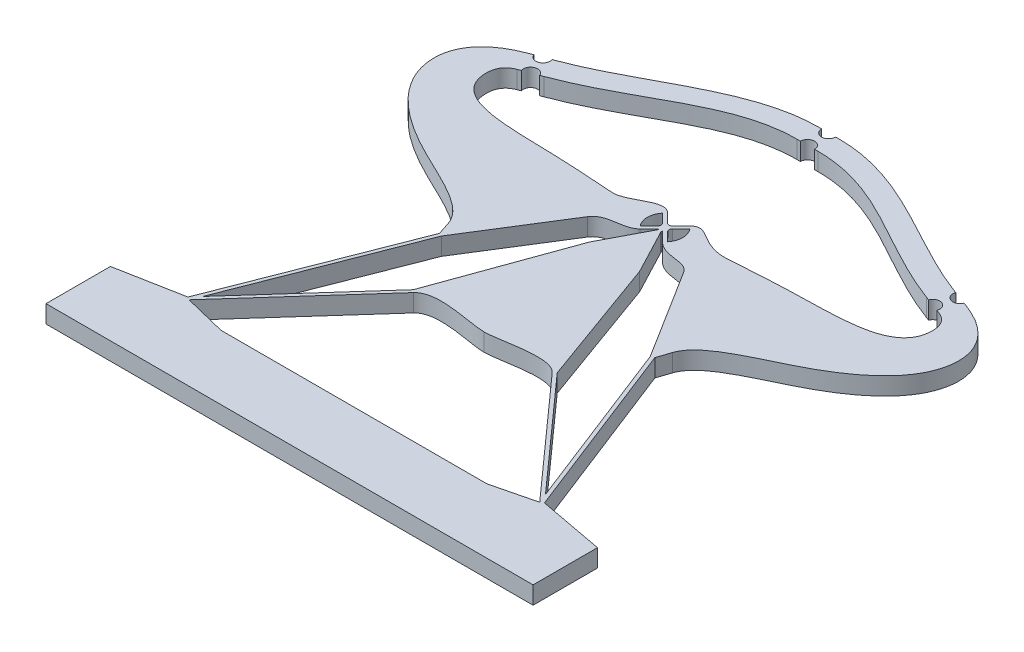
SolidWorks part; units mm, degrees
ref_plane "Front Plane" through (0, 0, 0) normal (0, 0, 1) x (1, 0, 0)
ref_plane "Top Plane" through (0, 0, 0) normal (0, 1, 0) x (1, 0, 0)
ref_plane "Right Plane" through (0, 0, 0) normal (1, 0, 0) x (0, 0, -1)
sketch "Basic" plane through (0, 0, 0) normal (0, 1, 0) x (1, 0, 0)
  line L0 (-100, 0) -> (-40, 67.082) construction
  line L1 (-40, 67.082) -> (0, 169.5515) construction
  line L2 (0, 169.5515) -> (-60, 102.4695) construction
  line L3 (-60, 102.4695) -> (-100, 0) construction
  line L4 (-40, 67.082) -> (40, 67.082) construction
  line L5 (-60, 102.4695) -> (-115.9233, 212.8627) construction
  line L6 (-115.9233, 212.8627) -> (0, 169.5515) construction
  line L7 (-115.9233, 212.8627) -> (0, 256.1738) construction
  line L8 (0, 256.1738) -> (0, 169.5515) construction
  line L9 (115.9233, 212.8627) -> (0, 256.1738) construction
  line L10 (115.9233, 212.8627) -> (0, 169.5515) construction
  line L11 (60, 102.4695) -> (115.9233, 212.8627) construction
  line L12 (60, 102.4695) -> (100, 0) construction
  line L13 (0, 169.5515) -> (60, 102.4695) construction
  line L14 (40, 67.082) -> (0, 169.5515) construction
  line L15 (100, 0) -> (40, 67.082) construction
  point P0 (-100, 0)
  point P1 (-40, 67.082)
  point P2 (0, 169.5515)
  point P14 (0, 67.082)
  point P15 (0, 0)
  dimension "l1/2" = 100
  dimension "l2" = 90
  dimension "l3/2" = 40
  dimension "couplerLength" = 110
  dimension "couplerAngle" = 68.676
  dimension "couplerAngle2" = 68.676
  dimension "D1" = 68.676
  dimension "OAngle" = 69.513
  dimension "D3" = 69.513
sketch "Sketch4" plane through (0, 0, 0) normal (0, 1, 0) x (1, 0, 0)
  line L0 (-100, 0) -> (-40, 67.082) construction
  line L1 (0, 256.1738) -> (0, 169.5515) construction
  line L2 (-60, 102.4695) -> (-100, 0) construction
  line L3 (-60.9315, 102.8331) -> (-100.9315, 0.3636)
  line L4 (-59.0685, 102.1059) -> (-97.0562, 4.7913)
  line L5 (-99.2546, -0.6667) -> (-39.2546, 66.4154)
  line L6 (-97.0562, 4.7913) -> (-40.7454, 67.7487)
  line L7 (-27.2733, 152.8134) -> (-59.0685, 102.1059)
  line L8 (-8.808, 205.2724) -> (8.808, 133.8307) construction
  line L9 (-100.9315, 0.3636) -> (-137.8734, -6.5819)
  line L10 (-8.989, 165.1701) -> (-28.2658, 154.55)
  line L11 (-99.2546, -0.6667) -> (-75.2651, -6.5819)
  line L12 (-6.4533, 162.591) -> (-40.7454, 67.7487)
  line L13 (-100.7454, 0.6667) -> (-40.7454, 67.7487) construction
  line L14 (-7.9358, 163.4669) -> (-27.2733, 152.8134)
  line L15 (0, 169.5515) -> (-60, 102.4695) construction
  line L16 (-115.9233, 212.8627) -> (0, 169.5515) construction
  line L17 (0, 169.5515) -> (42.4895, 180.0285) construction
  line L19 (-115.9233, 212.8627) -> (0, 256.1738) construction
  line L20 (-59.0685, 102.1059) -> (-99.0685, -0.3636) construction
  line L21 (-60.9315, 102.8331) -> (-63.4074, 110.2406)
  line L26 (-121.6167, 228.1012) -> (-109.5404, 195.7788) construction
  line L27 (-121.7702, 217.0832) -> (-123.6438, 216.3832)
  line L28 (-110.0763, 208.6421) -> (-108.2028, 209.3421)
  line L29 (-103.9501, 217.3361) -> (-126.2848, 208.9914) construction
  line L30 (-117.5704, 205.8422) -> (-119.4439, 205.1422)
  line L31 (-114.2762, 219.8831) -> (-112.4027, 220.5831)
  line L33 (-27.2733, 152.8134) -> (-7.9358, 163.4669)
  line L36 (-31.9283, 171.6919) -> (-9.8548, 171.2494)
  line L37 (-9.8548, 171.2494) -> (-31.9283, 171.6919)
  line L38 (12.8937, 256.1738) -> (-10.9489, 256.1738) construction
  line L39 (0, 265.543) -> (0, 231.0383) construction
  line L40 (4, 250.1738) -> (6, 250.1738) construction
  line L41 (4, 262.1738) -> (6, 262.1738) construction
  line L42 (-4, 250.1738) -> (-6, 250.1738)
  line L43 (-4, 262.1738) -> (-6, 262.1738)
  line L44 (-9.9955, 169.2518) -> (-31.9997, 169.693)
  line L54 (0, 185.8984) -> (-14.1025, 185.8984) construction
  line L55 (0, -6.5819) -> (-75.2651, -6.5819)
  line L56 (-137.8734, -6.5819) -> (-137.8734, -43.045)
  line L57 (-40, 67.082) -> (40, 67.082) construction
  line L58 (-137.8734, -43.045) -> (0, -43.045)
  line L60 (0, -6.5819) -> (0, -43.045)
  line L61 (0, 185.8984) -> (0, 67.082)
  line L62 (0, 258.1738) -> (0, 254.1738)
  arc A2 (-6.4533, 162.591) -> (-7.9358, 163.4669) centre (-7.4533, 162.591) ccw
  arc A5 (-31.9997, 169.693) -> (-28.2658, 154.55) centre (0, 169.5515) ccw
  arc A8 (-121.7702, 217.0832) -> (-114.2762, 219.8831) centre (-118.0232, 218.4832) ccw
  arc A9 (-117.5704, 205.8422) -> (-110.0763, 208.6421) centre (-113.8234, 207.2421) cw
  arc A12 (-4, 250.1738) -> (0, 254.1738) centre (0, 250.1738) cw
  arc A13 (-4, 262.1738) -> (0, 258.1738) centre (0, 262.1738) ccw
  arc A16 (-8.989, 165.1701) -> (-9.9955, 169.2518) centre (0, 169.5515) cw
  arc A17 (-8.9494, 172.7141) -> (-9.8548, 171.2494) centre (-9.8348, 172.2492) cw
  spline S0 degree 3 poles (-108.2028, 209.3421) (-69.2396, 223.8995) (-42.6858, 250.1738) (-6, 250.1738) knots 0 0 0 0 1 1 1 1
  spline S1 degree 3 poles (-112.4027, 220.5831) (-76.7304, 233.911) (-44.0894, 262.1738) (-6, 262.1738) knots 0 0 0 0 1 1 1 1
  spline S3 degree 3 poles (-119.4439, 205.1422) (-125.6717, 202.8154) (-131.1957, 172.2284) (-78.3016, 175.6405) (-35.272, 171.759) (-31.9283, 171.6919) knots 0 0 0 0 0.124419 0.71001 1 1 1 1
  spline S4 degree 3 poles (-123.6438, 216.3832) (-146.4506, 207.8622) (-156.0924, 174.1496) (-112.6778, 138.1204) (-67.7469, 123.2236) (-63.4074, 110.2406) knots 0 0 0 0 0.283699 0.638824 1 1 1 1
  spline S10 degree 3 poles (-39.2546, 66.4154) (-32.2633, 74.2319) (-8.577, 67.082) (0, 67.082) knots 0 0 0 0 1 1 1 1
  spline S11 degree 3 poles (-8.9494, 172.7141) (-10.9706, 176.5634) (-7.6165, 181.239) (-4.8136, 185.8984) (0, 185.8984) knots 0 0 0 0 0.470593 1 1 1 1
  dimension "D6" = 10
  dimension "D11" = 10.198
  dimension "D21" = 4
  dimension "D31" = 4
  dimension "D7" = 32
  dimension "D10" = 1
  dimension "D13" = 1
  dimension "D8" = 1
  dimension "D4" = 1
  dimension "D5" = 1
  dimension "D9" = 2
  dimension "D12" = 15
  dimension "D22" = 6
  dimension "D23" = 8
  dimension "D24" = 2
  dimension "D25" = 2
  dimension "D32" = 6
  dimension "D33" = 8
  dimension "D34" = 2
  dimension "D35" = 2
sketch "Sketch5" plane through (0, 0, 0) normal (0, 1, 0) x (1, 0, 0)
  line L0 (-14.0529, 35.7209) -> (3.5631, -35.7209) construction
  line L1 (-14.234, -4.3814) -> (-33.5107, -15.0015)
  line L2 (-13.1807, -6.0846) -> (-32.5182, -16.7382)
  line L3 (-5.2449, 0) -> (37.2446, 10.477) construction
  line L4 (-32.5182, -16.7382) -> (-13.1807, -6.0846)
  line L5 (-32.8384, 16.2049) -> (-13.6886, 5.3576)
  line L6 (-33.7969, 14.4493) -> (-14.5868, 3.5678)
  line L7 (-37.1732, 2.1404) -> (-15.0997, 1.6979)
  line L8 (-15.0997, 1.6979) -> (-37.1732, 2.1404)
  line L9 (-15.2404, -0.2997) -> (-37.2446, 0.1414)
  line L10 (-23.8067, -26.0665) -> (-11.8573, -7.5017)
  line L11 (-22.1418, -27.1752) -> (-10.23, -8.6688)
  arc A0 (-11.8573, -7.5017) -> (-13.1807, -6.0846) centre (-12.6982, -6.9605) ccw
  arc A1 (-14.234, -4.3814) -> (-13.1807, -6.0846) centre (-5.2449, 0) ccw
  arc A2 (-11.8573, -7.5017) -> (-10.23, -8.6688) centre (-5.2449, 0) ccw
  arc A3 (-33.5107, -15.0015) -> (-32.5182, -16.7382) centre (-5.2449, 0) ccw
  arc A4 (-23.8067, -26.0665) -> (-22.1418, -27.1752) centre (-5.2449, 0) ccw
  arc A5 (-33.7969, 14.4493) -> (-32.8384, 16.2049) centre (-5.2449, 0) cw
  arc A6 (-37.2446, 0.1414) -> (-37.1732, 2.1404) centre (-5.2449, 0) cw
  arc A7 (-14.5868, 3.5678) -> (-13.6886, 5.3576) centre (-5.2449, 0) cw
  arc A8 (-14.234, -4.3814) -> (-15.2404, -0.2997) centre (-5.2449, 0) cw
  arc A9 (-14.5868, 3.5678) -> (-15.0997, 1.6979) centre (-15.0797, 2.6977) cw
  point P8 (-16.1859, -17.922)
  dimension "D1" = 64
  dimension "D4" = 1
  dimension "D7" = 10
  dimension "D2" = 2
  dimension "D3" = 2
  dimension "D5" = 10.198
  dimension "D6" = 15
extrude "Boss-Extrude1" add sketch "Sketch4" along normal blind 10
mirror "Mirror1" about plane through (0, 10, 0) normal (1, 0, 0) of bodies 101
sketch "Sketch6" plane through (0, 10, 0) normal (0, 1, 0) x (1, 0, 0)
  circle A0 centre (0, 169.5515) radius 32
extrude "Cut-Extrude1" cut sketch "Sketch6" against normal blind 10 contours A0
sketch "Sketch7" plane through (0, 10, 0) normal (0, 1, 0) x (1, 0, 0)
  line L0 (-7.0711, 176.6226) -> (7.0711, 162.4805) construction
  line L1 (-27.2733, 152.8134) -> (-59.0685, 102.1059) construction
  line L2 (7.0711, 176.6226) -> (-7.0711, 162.4805) construction
  line L4 (1, 166.2325) -> (14.2892, 140.9191)
  line L5 (6.364, 177.3297) -> (1.4142, 172.38)
  line L6 (-7.7782, 175.9155) -> (-2.8284, 170.9658)
  line L7 (7.7782, 175.9155) -> (2.8284, 170.9658)
  line L8 (-6.364, 177.3297) -> (-1.4142, 172.38)
  line L9 (1.4142, 166.7231) -> (6.364, 161.7734)
  line L10 (-2.8284, 168.1373) -> (-7.7782, 163.1876)
  line L11 (-7.7782, 175.9155) -> (6.364, 161.7734) construction
  line L12 (2.8284, 168.1373) -> (7.7782, 163.1876)
  line L13 (6.364, 177.3297) -> (-7.7782, 163.1876) construction
  line L14 (-1.4142, 166.7231) -> (-6.364, 161.7734)
  line L15 (-6.364, 177.3297) -> (7.7782, 163.1876) construction
  line L16 (27.2733, 152.8134) -> (59.0685, 102.1059) construction
  line L17 (7.7782, 175.9155) -> (-6.364, 161.7734) construction
  line L18 (-1, 166.2325) -> (-14.2892, 140.9191)
  line L20 (-1, 166.2325) -> (-1, 167.041)
  line L22 (1, 166.2325) -> (1, 167.041)
  line L23 (-1, 163.0509) -> (1, 167.5669) construction
  line L24 (-1, 167.5669) -> (1, 163.0509) construction
  arc A0 (-31.9283, 171.6919) -> (-27.2733, 152.8134) centre (0, 169.5515) ccw construction
  arc A1 (27.2733, 152.8134) -> (31.9283, 171.6919) centre (0, 169.5515) ccw construction
  arc A2 (7.7427, 163.223) -> (7.7427, 175.8801) centre (0, 169.5515) ccw
  arc A3 (-7.7427, 175.8801) -> (-7.7427, 163.223) centre (0, 169.5515) ccw
  arc A4 (27.2733, 152.8134) -> (31.9283, 171.6919) centre (0, 169.5515) ccw
  arc A5 (-31.9283, 171.6919) -> (-27.2733, 152.8134) centre (0, 169.5515) ccw
  arc A6 (-14.2892, 140.9191) -> (14.2892, 140.9191) centre (0, 169.5515) ccw construction
  arc A7 (-14.2892, 140.9191) -> (14.2892, 140.9191) centre (0, 169.5515) ccw
  arc A8 (-2.8284, 168.1373) -> (-2.8284, 170.9658) centre (-4.2426, 169.5515) ccw
  arc A9 (-1.4142, 172.38) -> (1.4142, 172.38) centre (0, 173.7942) ccw
  arc A10 (2.8284, 170.9658) -> (2.8284, 168.1373) centre (4.2426, 169.5515) ccw
  arc A11 (1.4142, 166.7231) -> (1, 167.041) centre (0, 165.3089) ccw
  arc A12 (-1, 167.041) -> (-1.4142, 166.7231) centre (0, 165.3089) ccw
  spline S0 degree 3 poles (6.364, 177.3297) (12.5034, 183.4691) (17.4314, 171.4013) (31.9283, 171.6919) knots 0 0 0 0 1 1 1 1
  spline S1 degree 3 poles (119.4439, 205.1422) (125.6717, 202.8154) (131.1957, 172.2284) (78.3016, 175.6405) (35.272, 171.759) (31.9283, 171.6919) knots 0 0 0 0 0.124419 0.71001 1 1 1 1 construction
  spline S2 degree 3 poles (6.364, 161.7734) (13.428, 154.7094) (23.2328, 159.2574) (27.2733, 152.8134) knots 0 0 0 0 1 1 1 1
  spline S3 degree 3 poles (-31.9283, 171.6919) (-23.2039, 171.517) (-12.8704, 183.8362) (-6.364, 177.3297) knots 0 0 0 0 1 1 1 1
  spline S4 degree 3 poles (-27.2733, 152.8134) (-22.7049, 160.0991) (-11.7258, 156.4116) (-6.364, 161.7734) knots 0 0 0 0 1 1 1 1
  spline S5 degree 3 poles (-119.4439, 205.1422) (-125.6717, 202.8154) (-131.1957, 172.2284) (-78.3016, 175.6405) (-35.272, 171.759) (-31.9283, 171.6919) knots 0 0 0 0 0.124419 0.71001 1 1 1 1 construction
  point P31 (-1.4142, 169.5515)
  point P37 (0, 181.9657)
  point P39 (0, 170.9658)
  dimension "D1" = 2
  dimension "D4" = 2
  dimension "D2" = 1
  dimension "D3" = 1
extrude "Boss-Extrude3" add sketch "Sketch7" against normal blind 10
equation "\"couplerAngle\"= \"couplerAngle@Basic\""
equation "\"couplerAngle2@Basic\"=\"couplerAngle\""
equation "\"D1@Basic\"=\"couplerAngle\""
equation "\"OAngle\"= \"OAngle@Basic\""
equation "\"D3@Basic\"=\"OAngle\""
equation "\"beta\"= 0.25"
equation "\"t\"= 2mm"
equation "\"D\"= \"t\" / \"beta\""
